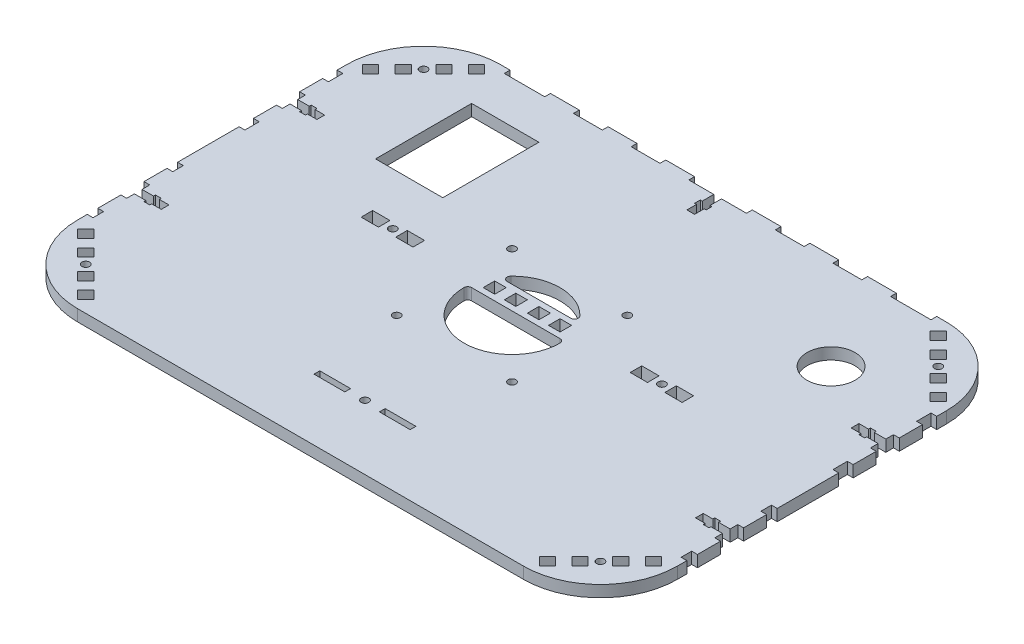
SolidWorks part; units mm, degrees
ref_plane "Plan de face" through (0, 0, 0) normal (0, 0, 1) x (1, 0, 0)
ref_plane "Plan de dessus" through (0, 0, 0) normal (0, 1, 0) x (1, 0, 0)
ref_plane "Plan de droite" through (0, 0, 0) normal (1, 0, 0) x (0, 0, -1)
sketch "Esquisse1" plane through (0, 0, 0) normal (0, 1, 0) x (1, 0, 0)
  line L1 (-156, 220) -> (156, 220)
  line L2 (-156, 220) -> (-156, 0)
  line L3 (-156, 0) -> (156, 0)
  line L4 (156, 220) -> (156, 0)
  dimension "D1" = 312
  dimension "D2" = 220
extrude "Boss.-Extru.1" add sketch "Esquisse1" along normal blind 6
fillet "Congé1" radius 40 4 edges at (-156, 3, -220) (156, 3, -220) (156, 3, 0) (-156, 3, 0)
sketch "Esquisse2" plane through (0, 0, 0) normal (0, -1, 0) x (1, 0, 0)
  line L0 (-156, -40) -> (-116, 0) construction
  line L1 (-136, -20) -> (-126.4019, -29.5981) construction
  line L2 (-120.0901, -4.0901) -> (-124.3327, -8.3327)
  line L3 (-120.0901, -4.0901) -> (-115.8475, -8.3327)
  line L4 (-124.3327, -8.3327) -> (-120.0901, -12.5754)
  line L5 (-115.8475, -8.3327) -> (-120.0901, -12.5754)
  line L6 (-128.5754, -12.5754) -> (-132.818, -16.818)
  line L7 (-128.5754, -12.5754) -> (-124.3327, -16.818)
  line L8 (-132.818, -16.818) -> (-128.5754, -21.0607)
  line L9 (-124.3327, -16.818) -> (-128.5754, -21.0607)
  line L10 (-139.182, -23.182) -> (-143.4246, -27.4246)
  line L11 (-139.182, -23.182) -> (-134.9393, -27.4246)
  line L12 (-143.4246, -27.4246) -> (-139.182, -31.6673)
  line L13 (-134.9393, -27.4246) -> (-139.182, -31.6673)
  line L14 (-147.6673, -31.6673) -> (-151.9099, -35.9099)
  line L15 (-147.6673, -31.6673) -> (-143.4246, -35.9099)
  line L16 (-151.9099, -35.9099) -> (-147.6673, -40.1525)
  line L17 (-143.4246, -35.9099) -> (-147.6673, -40.1525)
  line L18 (-130.6967, -18.9393) -> (-137.0607, -25.3033) construction
  circle A0 centre (-133.8787, -22.1213) radius 2
  dimension "D9" = 4
  dimension "D1" = 6
  dimension "D2" = 6
  dimension "D3" = 6
  dimension "D4" = 9
  dimension "D5" = 6
  dimension "D6" = 6
  dimension "D7" = 6
  dimension "D8" = 6
extrude "Enlèv. mat.-Extru.1" cut sketch "Esquisse2" against normal blind 6
ref_plane "Plan1" through (0, 0, 0) normal (-1, 0, 0) x (0, 0, 1)
mirror "Symétrie1" about plane through (0, 0, 0) normal (-1, 0, 0) of "Enlèv. mat.-Extru.1"
sketch "Esquisse3" plane through (0, 0, 0) normal (0, -1, 0) x (-1, 0, 0)
  line L0 (0, 0) -> (0, 220) construction
  line L1 (-116, 220) -> (116, 220) construction
  line L2 (-156, 115) -> (156, 115) construction
  line L3 (-156, 40) -> (-156, 180) construction
  line L4 (156, 180) -> (156, 40) construction
  line L5 (116, 0) -> (-116, 0) construction
  line L6 (-74.5, 118) -> (-65.5, 118) construction
  line L7 (-3, 115) -> (-9, 115)
  line L8 (-3, 115) -> (-3, 121)
  line L9 (-3, 121) -> (-9, 121)
  line L10 (-9, 115) -> (-9, 121)
  line L11 (-14, 115) -> (-20, 115)
  line L12 (-14, 115) -> (-14, 121)
  line L13 (-14, 121) -> (-20, 121)
  line L14 (-20, 115) -> (-20, 121)
  line L15 (-56.5, 115) -> (-65.5, 115)
  line L16 (-56.5, 115) -> (-56.5, 121)
  line L17 (-56.5, 121) -> (-65.5, 121)
  line L18 (-65.5, 115) -> (-65.5, 121)
  line L19 (-74.5, 115) -> (-83.5, 115)
  line L21 (-74.5, 115) -> (-74.5, 121)
  line L22 (-74.5, 121) -> (-83.5, 121)
  line L23 (-83.5, 115) -> (-83.5, 121)
  circle A0 centre (-70, 118) radius 2
  dimension "D1" = 115
  dimension "D2" = 9
  dimension "D9" = 3
  dimension "D10" = 4
  dimension "D3" = 5
  dimension "D4" = 6
  dimension "D5" = 6
  dimension "D6" = 9
  dimension "D7" = 9
  dimension "D8" = 6
  dimension "D11" = 36.5
extrude "Enlèv. mat.-Extru.2" cut sketch "Esquisse3" against normal blind 6
sketch "Esquisse4" plane through (0, 6, 0) normal (0, 1, 0) x (1, 0, 0)
  line L0 (156, 175) -> (118.0825, 175) construction
  line L1 (156, 40) -> (156, 180) construction
  line L2 (156, 124) -> (118.0825, 124) construction
  line L3 (153, 45) -> (153, 92) construction
  line L4 (156, 45) -> (118.0825, 45) construction
  line L5 (156, 92) -> (118.0825, 92) construction
  line L6 (153, 124) -> (153, 175) construction
  line L7 (153, 68.5) -> (162.1582, 68.5) construction
  line L8 (153, 149.5) -> (165.7667, 149.5) construction
  line L10 (153, 45) -> (156, 45)
  line L11 (153, 45) -> (153, 50.5)
  line L12 (153, 50.5) -> (156, 50.5)
  line L13 (156, 45) -> (156, 50.5)
  line L14 (153, 62.5) -> (156, 62.5)
  line L15 (153, 62.5) -> (153, 74.5)
  line L16 (153, 74.5) -> (156, 74.5)
  line L17 (156, 62.5) -> (156, 74.5)
  line L18 (153, 92) -> (156, 92)
  line L19 (153, 92) -> (153, 86.5)
  line L20 (153, 86.5) -> (156, 86.5)
  line L21 (156, 92) -> (156, 86.5)
  line L22 (153, 124) -> (156, 124)
  line L23 (153, 124) -> (153, 131.5)
  line L24 (153, 131.5) -> (156, 131.5)
  line L25 (156, 124) -> (156, 131.5)
  line L26 (153, 175) -> (156, 175)
  line L27 (153, 175) -> (153, 167.5)
  line L28 (153, 167.5) -> (156, 167.5)
  line L29 (156, 175) -> (156, 167.5)
  line L30 (153, 143.5) -> (156, 143.5)
  line L31 (153, 143.5) -> (153, 155.5)
  line L32 (153, 155.5) -> (156, 155.5)
  line L33 (156, 143.5) -> (156, 155.5)
  dimension "D1" = 51
  dimension "D2" = 47
  dimension "D3" = 5
  dimension "D4" = 5
  dimension "D5" = 3
  dimension "D6" = 12
  dimension "D7" = 12
  dimension "D8" = 12
  dimension "D9" = 12
  dimension "D10" = 12
  dimension "D11" = 12
extrude "Enlèv. mat.-Extru.3" cut sketch "Esquisse4" against normal blind 6
sketch "Esquisse5" plane through (0, 6, 0) normal (0, 1, 0) x (1, 0, 0)
  line L0 (153, 68.5) -> (107.7882, 68.5) construction
  line L1 (153, 74.5) -> (153, 62.5) construction
  line L2 (153, 149.5) -> (128.3286, 149.5) construction
  line L3 (144, 147.5) -> (144, 146.5)
  line L4 (153, 151.5) -> (147, 151.5)
  line L5 (153, 151.5) -> (153, 147.5)
  line L6 (153, 147.5) -> (147, 147.5)
  line L7 (147, 147.5) -> (147, 146.5)
  line L8 (147, 152.5) -> (144, 152.5)
  line L9 (147, 152.5) -> (147, 151.5)
  line L10 (147, 146.5) -> (144, 146.5)
  line L11 (144, 152.5) -> (144, 151.5)
  line L12 (139, 151.5) -> (144, 151.5)
  line L13 (139, 151.5) -> (139, 147.5)
  line L14 (144, 66.5) -> (144, 65.5)
  line L15 (153, 70.5) -> (147, 70.5)
  line L16 (153, 70.5) -> (153, 66.5)
  line L17 (153, 66.5) -> (147, 66.5)
  line L18 (147, 66.5) -> (147, 65.5)
  line L19 (147, 71.5) -> (144, 71.5)
  line L20 (147, 71.5) -> (147, 70.5)
  line L21 (147, 65.5) -> (144, 65.5)
  line L22 (144, 71.5) -> (144, 70.5)
  line L23 (139, 70.5) -> (144, 70.5)
  line L24 (139, 70.5) -> (139, 66.5)
  line L25 (139, 66.5) -> (144, 66.5)
  line L26 (139, 147.5) -> (144, 147.5)
  line L28 (153, 155.5) -> (153, 143.5) construction
  dimension "D2" = 4
  dimension "D3" = 5
  dimension "D4" = 3
  dimension "D5" = 1
  dimension "D6" = 4
  dimension "D7" = 6
  dimension "D8" = 5
  dimension "D9" = 3
  dimension "D10" = 1
  dimension "D11" = 6
extrude "Enlèv. mat.-Extru.4" cut sketch "Esquisse5" against normal blind 6
mirror "Symétrie2" about plane through (0, 0, 0) normal (-1, 0, 0) of "Enlèv. mat.-Extru.3", "Enlèv. mat.-Extru.4", "Enlèv. mat.-Extru.2"
ref_plane "Plan2" through (0, 0, -110) normal (0, 0, 1) x (1, 0, 0)
mirror "Symétrie3" about plane through (0, 0, -110) normal (0, 0, 1) of "Symétrie1", "Enlèv. mat.-Extru.1"
sketch "Esquisse6" plane through (0, 6, 0) normal (0, 1, 0) x (1, 0, 0)
  line L0 (0, 220) -> (0, 134.5606) construction
  line L1 (116, 220) -> (-116, 220) construction
  line L2 (114.2161, 217) -> (-111, 217) construction
  line L3 (-114.2161, 217) -> (111, 217) construction
  line L4 (15, 217) -> (2, 217)
  line L5 (111, 217) -> (111, 220)
  line L6 (15, 220) -> (-15, 220)
  line L7 (-15, 217) -> (-15, 220)
  line L8 (-30, 217) -> (-45, 217)
  line L9 (-30, 217) -> (-30, 220)
  line L10 (-30, 220) -> (-45, 220)
  line L11 (-45, 217) -> (-45, 220)
  line L12 (-60, 217) -> (-75, 217)
  line L13 (-60, 217) -> (-60, 220)
  line L14 (-60, 220) -> (-75, 220)
  line L15 (-75, 217) -> (-75, 220)
  line L16 (-90, 217) -> (-111, 217)
  line L17 (-90, 217) -> (-90, 220)
  line L18 (-90, 220) -> (-111, 220)
  line L19 (-111, 217) -> (-111, 220)
  line L20 (90, 220) -> (111, 220)
  line L21 (90, 217) -> (90, 220)
  line L22 (90, 217) -> (111, 217)
  line L23 (75, 217) -> (75, 220)
  line L24 (60, 220) -> (75, 220)
  line L25 (60, 217) -> (60, 220)
  line L26 (60, 217) -> (75, 217)
  line L27 (45, 217) -> (45, 220)
  line L28 (30, 220) -> (45, 220)
  line L29 (30, 217) -> (30, 220)
  line L30 (30, 217) -> (45, 217)
  line L31 (15, 217) -> (15, 220)
  line L32 (-2, 211) -> (-3, 211)
  line L34 (-2, 217) -> (-2, 211)
  line L35 (-2, 208) -> (-3, 208)
  line L36 (2, 217) -> (2, 211)
  line L37 (3, 211) -> (2, 211)
  line L38 (3, 211) -> (3, 208)
  line L39 (3, 208) -> (2, 208)
  line L40 (-3, 211) -> (-3, 208)
  line L41 (-2, 217) -> (-15, 217)
  line L42 (-2, 208) -> (-2, 203)
  line L43 (-2, 203) -> (2, 203)
  line L44 (2, 208) -> (2, 203)
  point P36 (0, 217)
  dimension "D1" = 3
  dimension "D2" = 15
  dimension "D3" = 15
  dimension "D4" = 15
  dimension "D5" = 21
  dimension "D6" = 15
  dimension "D7" = 15
  dimension "D8" = 15
  dimension "D9" = 6
  dimension "D10" = 5
  dimension "D11" = 3
  dimension "D12" = 4
  dimension "D13" = 1
extrude "Enlèv. mat.-Extru.5" cut sketch "Esquisse6" against normal blind 6
sketch "Esquisse7" plane through (0, 6, 0) normal (0, 1, 0) x (1, 0, 0)
  line L0 (-75, 220) -> (-90, 220) construction
  line L2 (156, 155.5) -> (156, 167.5) construction
  line L3 (-75, 220) -> (-90, 220) construction
  line L4 (-106, 145) -> (-71, 145)
  line L5 (-106, 145) -> (-106, 195)
  line L6 (-106, 195) -> (-71, 195)
  line L7 (-71, 145) -> (-71, 195)
  line L8 (-156, 167.5) -> (-156, 155.5) construction
  circle A0 centre (106, 170) radius 12.5
  dimension "D1" = 25
  dimension "D2" = 50
  dimension "D3" = 50
  dimension "D4" = 35
  dimension "D5" = 50
  dimension "D6" = 25
  dimension "D7" = 50
extrude "Enlèv. mat.-Extru.6" cut sketch "Esquisse7" against normal blind 6
sketch "Esquisse8" plane through (0, 0, 0) normal (0, -1, 0) x (1, 0, 0)
  line L0 (0, -203) -> (0, 0) construction
  line L2 (-2, -203) -> (2, -203) construction
  line L3 (37.703, -32) -> (-35.8927, -32) construction
  line L4 (37.703, -35) -> (-35.8927, -35) construction
  line L5 (9, -35) -> (25, -35)
  line L6 (25, -35) -> (25, -32)
  line L7 (9, -32) -> (9, -35)
  line L8 (25, -32) -> (9, -32)
  line L9 (-9, -32) -> (-9, -35)
  line L10 (-9, -35) -> (-25, -35)
  line L11 (-25, -35) -> (-25, -32)
  line L12 (-25, -32) -> (-9, -32)
  line L13 (9, -33.5) -> (-9, -33.5) construction
  line L15 (-116, 0) -> (116, 0) construction
  circle A0 centre (0, -33.5) radius 2
  dimension "D3" = 4
  dimension "D1" = 3
  dimension "D2" = 18
  dimension "D4" = 16
  dimension "D5" = 16
  dimension "D6" = 35
extrude "Enlèv. mat.-Extru.7" cut sketch "Esquisse8" against normal blind 6
sketch "Esquisse9" plane through (0, 6, 0) normal (0, 1, 0) x (1, 0, 0)
  line L0 (156, 0) -> (-156, 220) construction
  line L1 (-156, 0) -> (156, 220) construction
  line L2 (-116, 0) -> (116, 0) construction
  line L3 (156, 92) -> (156, 124) construction
  line L4 (-156, 124) -> (-156, 92) construction
  line L5 (-75, 220) -> (-90, 220) construction
  line L7 (90, 220) -> (75, 220) construction
  line L8 (0, 110) -> (0, 70) construction
  line L9 (-40, 70) -> (-40, 150) construction
  line L10 (-40, 150) -> (40, 150) construction
  line L11 (40, 150) -> (40, 70) construction
  line L12 (40, 70) -> (0, 70) construction
  line L13 (0, 70) -> (-40, 70) construction
  circle A0 centre (30, 80) radius 2
  circle A1 centre (-30, 80) radius 2
  circle A2 centre (-30, 140) radius 2
  circle A3 centre (30, 140) radius 2
  dimension "D5" = 4
  dimension "D8" = 4
  dimension "D9" = 4
  dimension "D10" = 4
  dimension "D1" = 40
  dimension "D2" = 40
  dimension "D3" = 80
  dimension "D4" = 40
  dimension "D6" = 10
  dimension "D7" = 10
  dimension "D11" = 10
  dimension "D12" = 10
  dimension "D13" = 10
  dimension "D14" = 10
  dimension "D15" = 10
  dimension "D16" = 10
extrude "Enlèv. mat.-Extru.8" cut sketch "Esquisse9" against normal blind 6
sketch "Esquisse10" plane through (0, 6, 0) normal (0, 1, 0) x (1, 0, 0)
  line L0 (30, 80) -> (-30, 140) construction
  line L1 (-30, 140) -> (-30, 80) construction
  line L2 (-30, 80) -> (30, 140) construction
  line L3 (-24.9199, 112) -> (24.9199, 112)
  line L4 (9, 115) -> (3, 115) construction
  line L5 (20.7123, 124) -> (-20.7123, 124)
  line L6 (3, 121) -> (9, 121) construction
  arc A0 (20.7123, 124) -> (-20.7123, 124) centre (0, 110) ccw
  arc A1 (-24.9199, 112) -> (24.9199, 112) centre (0, 110) ccw
  dimension "D1" = 50
  dimension "D2" = 3
  dimension "D3" = 3
extrude "Enlèv. mat.-Extru.9" cut sketch "Esquisse10" against normal blind 6
fillet "Congé2" radius 2 4 edges at (24.9199, 3, -112) (-24.9199, 3, -112) (-20.7123, 3, -124) (20.7123, 3, -124)
